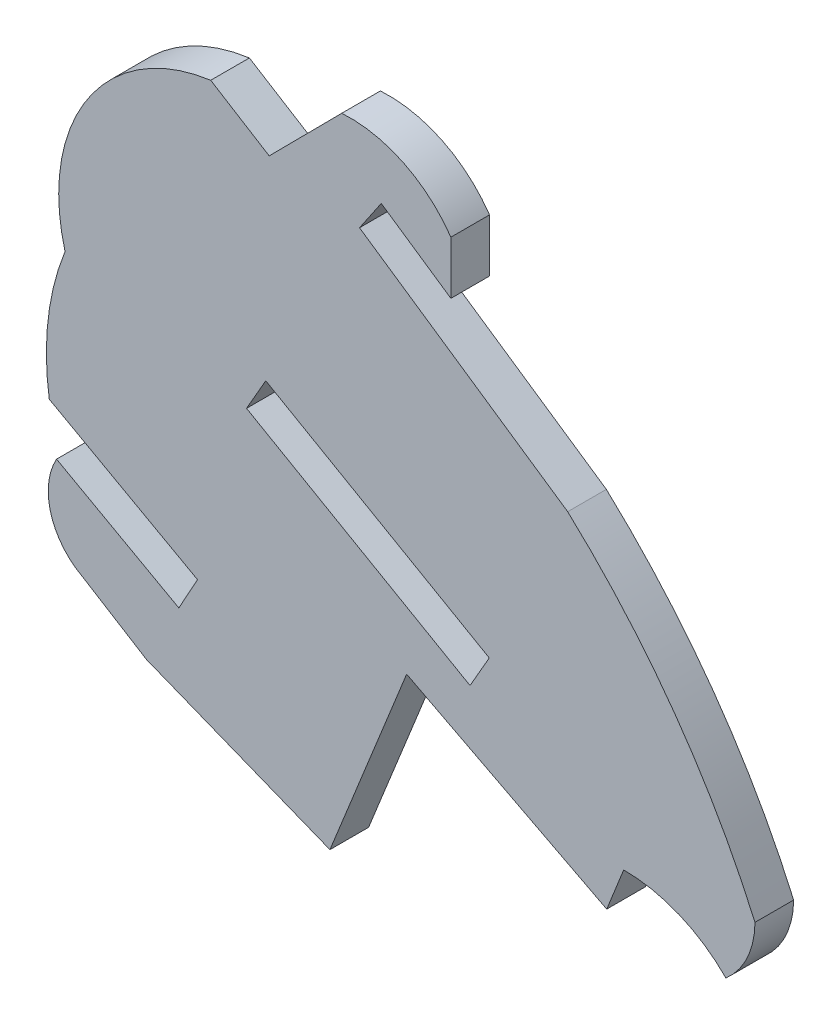
SolidWorks part; units mm, degrees
ref_plane "Front" through (0, 0, 0) normal (0, 0, 1) x (1, 0, 0)
ref_plane "Top" through (0, 0, 0) normal (0, 1, 0) x (1, 0, 0)
ref_plane "Right" through (0, 0, 0) normal (1, 0, 0) x (0, 0, -1)
sketch "Sketch1" plane through (0, 0, 0) normal (0, 0, 1) x (1, 0, 0)
  line L0 (254.459, 72.4241) -> (254.459, 68.3122)
  line L1 (247.3683, 69.5121) -> (263.5239, 58.5079)
  line L2 (249.0571, 71.9916) -> (254.459, 68.3122)
  line L3 (266.554, 33.309) -> (267.8712, 36.6039)
  line L4 (233.3457, 36.9502) -> (223.8566, 42.2059)
  line L5 (223.29, 45.9491) -> (234.7992, 39.5745)
  line L6 (230.8272, 32.2335) -> (245.0726, 26.5658)
  line L7 (225.8976, 35.2914) -> (230.8272, 32.2335)
  line L8 (234.7992, 39.5745) -> (233.3457, 36.9502)
  line L9 (245.0726, 26.5658) -> (251.0272, 41.3388)
  line L10 (251.0272, 41.3388) -> (266.554, 33.309)
  line L11 (240.0933, 55.5918) -> (257.4386, 45.6349)
  line L13 (238.5998, 52.99) -> (255.9451, 43.0331)
  line L14 (238.5998, 52.99) -> (240.0933, 55.5918)
  line L16 (255.9451, 43.0331) -> (257.4386, 45.6349)
  line L19 (235.8214, 73.6515) -> (240.3585, 70.8378)
  line L20 (247.3683, 69.5121) -> (249.0571, 71.9916)
  line L21 (240.3585, 70.8378) -> (245.99, 76.5199)
  arc A0 (235.8214, 73.6515) -> (224.5165, 56.4908) centre (237.6763, 60.1255) ccw
  arc A1 (278.0598, 38.1749) -> (263.5239, 58.5079) centre (221.9349, 13.414) ccw
  arc A2 (223.8566, 42.2059) -> (225.8976, 35.2914) centre (228.2428, 39.7421) ccw
  arc A3 (224.5165, 56.4908) -> (223.29, 45.9491) centre (243.3429, 48.9582) ccw
  arc A4 (275.8015, 33.3053) -> (267.8712, 36.6039) centre (267.9041, 25.5009) ccw
  arc A5 (275.8015, 33.3053) -> (278.0598, 38.1749) centre (271.6065, 38.2092) ccw
  arc A6 (254.459, 72.4241) -> (245.99, 76.5199) centre (246.6219, 67.0228) ccw
  dimension "D12" = 8
  dimension "D1" = 3
  dimension "D2" = 3
  dimension "D3" = 90
  dimension "D4" = 90
  dimension "D5" = 90
  dimension "D6" = 90
  dimension "D7" = 3
  dimension "D8" = 90
  dimension "D9" = 90
  dimension "D10" = 3
  dimension "D11" = 20
extrude "Base-Extrude" add sketch "Sketch1" along normal blind 3
